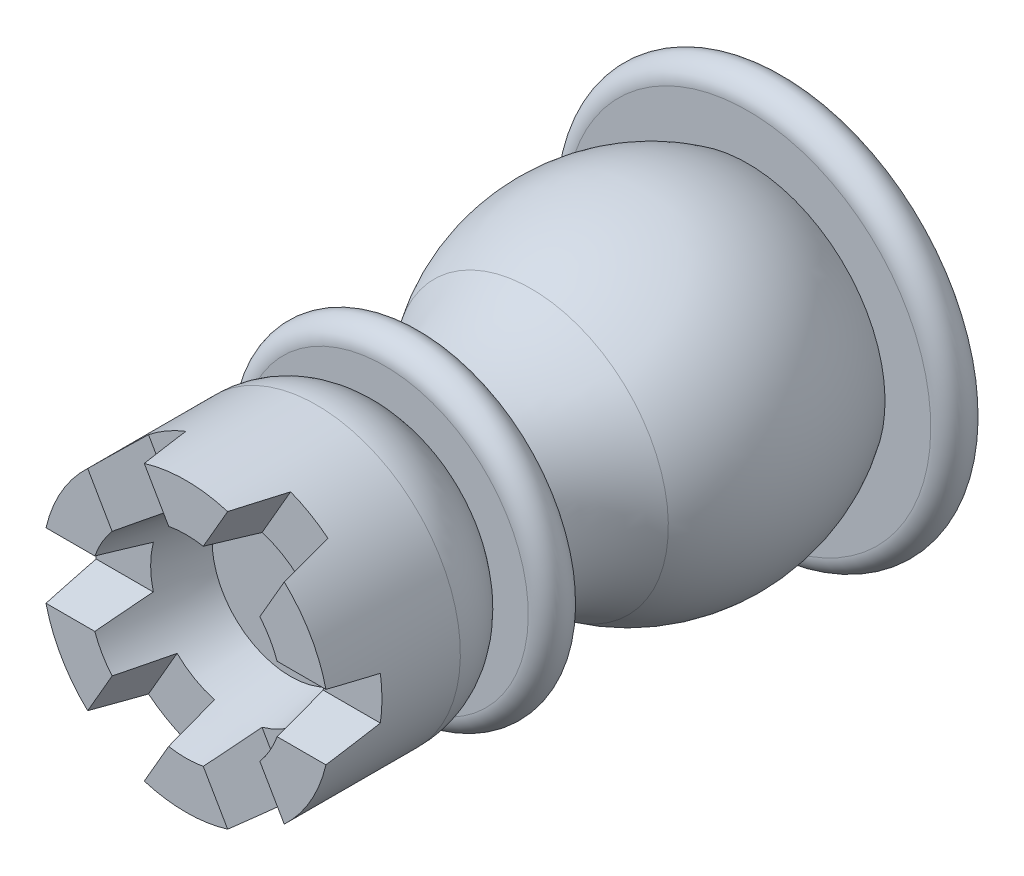
SolidWorks part; units mm, degrees
ref_plane "Front Plane" through (0, 0, 0) normal (1, 0, 0) x (0, 1, 0)
ref_plane "Top Plane" through (0, 0, 0) normal (0, 0, 1) x (0, 1, 0)
ref_plane "Right Plane" through (0, 0, 0) normal (0, 1, 0) x (-1, 0, 0)
sketch "Sketch1" plane through (0, 0, 0) normal (1, 0, 0) x (0, 1, 0)
  line L0 (0, 0) -> (14, 0)
  line L1 (14, 3) -> (10.5, 3)
  line L2 (8, 27.8038) -> (11, 27.8038)
  line L3 (11, 30.8038) -> (8, 30.8038)
  line L4 (11, 36) -> (11, 46)
  line L5 (11, 46) -> (7.4106, 46)
  line L6 (0, 38) -> (0, 0)
  line L7 (0, 38) -> (6, 38)
  line L8 (6, 38) -> (7.4106, 46)
  line L9 (7.4106, 46) -> (0, 46) construction
  line L10 (0, 46) -> (0, 38) construction
  arc A0 (14, 0) -> (14, 3) centre (14, 1.5) ccw
  arc A1 (10.5, 3) -> (10.4999, 19.5833) centre (-2, 11.2916) ccw
  arc A2 (10.4999, 19.5833) -> (8, 27.8038) centre (22.9998, 27.8749) cw
  arc A3 (11, 27.8038) -> (11, 30.8038) centre (11, 29.3038) ccw
  arc A5 (11, 36) -> (8, 30.8038) centre (5, 36) cw
  point P13 (0, 0)
  point P20 (13, 11.2916)
  point P23 (11, 30.5786)
  point P24 (0, 0)
  point P25 (8, 31.4344)
  point P26 (11, 36.0172)
  point P27 (0, 0)
  dimension "D4" = 15
  dimension "D5" = 15
  dimension "D6" = 1.5
  dimension "D12" = 1.5
  dimension "D15" = 2
  dimension "D14" = 6
  dimension "D1" = 46
  dimension "D2" = 10
  dimension "D3" = 12
  dimension "D7" = 28
  dimension "D8" = 21
  dimension "D9" = 16
  dimension "D10" = 26
  dimension "D11" = 22
  dimension "D13" = 8
revolve "Revolve1" add sketch "Sketch1" angle 360 about L10
sketch "Sketch2" plane through (0, 0, 0) normal (1, 0, 0) x (0, 1, 0)
  line L0 (0, 46) -> (0, 42) construction
  line L1 (7.4106, 46) -> (-7.4106, 46) construction
  line L2 (-1.6498, 42) -> (1.6498, 42)
  line L3 (1.6498, 42) -> (2.5, 46)
  line L4 (11, 46) -> (-11, 46) construction
  line L5 (2.5, 46) -> (-2.5, 46)
  line L6 (-1.6498, 42) -> (-2.5, 46)
  dimension "D1" = 24
  dimension "D2" = 4
  dimension "D3" = 5
extrude "Cut-Extrude1" cut sketch "Sketch2" against normal through all both and the other way through all
pattern_circular "CirPattern1" count 6 over 360 about axis through (0, 0, 0) along (0, 0, 1) of "Cut-Extrude1"
